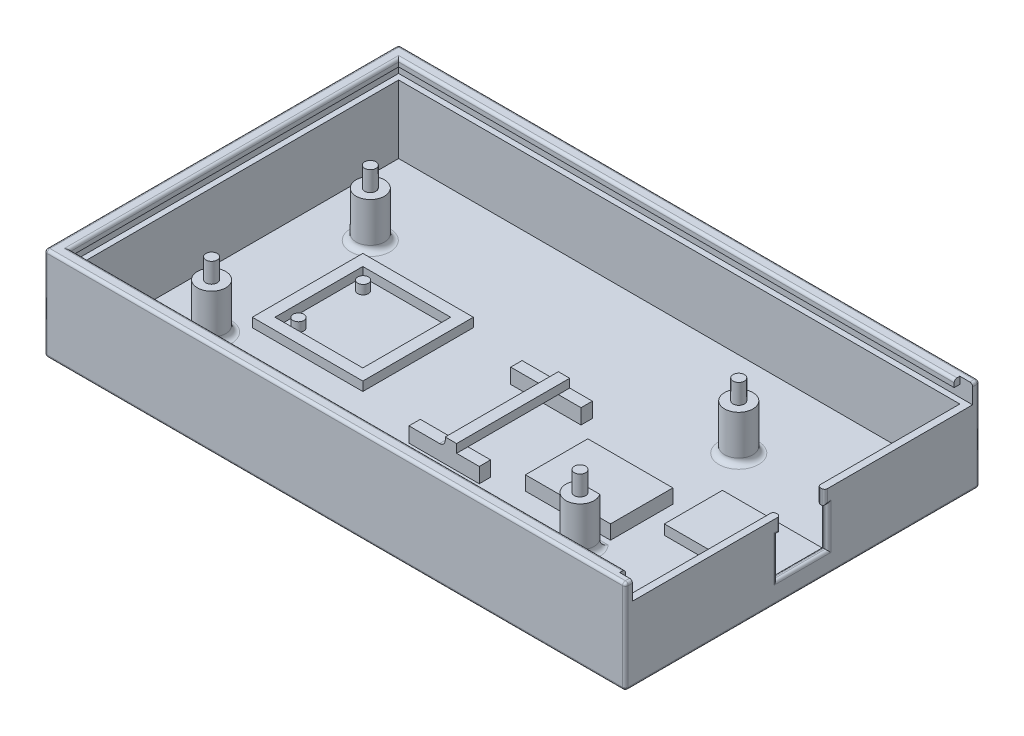
SolidWorks part; units mm, degrees
ref_plane "正面" through (0, 0, 0) normal (0, 0, 1) x (1, 0, 0)
ref_plane "平面" through (0, 0, 0) normal (0, 1, 0) x (1, 0, 0)
ref_plane "右側面" through (0, 0, 0) normal (1, 0, 0) x (0, 0, -1)
sketch "ｽｹｯﾁ1" plane through (0, 0, 0) normal (0, 1, 0) x (1, 0, 0)
  line L1 (-50, -30) -> (50, -30)
  line L2 (-50, -30) -> (-50, 30)
  line L3 (-50, 30) -> (50, 30)
  line L4 (50, -30) -> (50, 30)
  line L5 (-50, -30) -> (50, 30) construction
  line L6 (-50, 30) -> (50, -30) construction
  circle A0 centre (-32.7055, 14.1816) radius 1.25 construction
  circle A1 centre (32.2945, 14.1816) radius 1.25 construction
  circle A2 centre (32.2945, -13.8184) radius 1.25 construction
  circle A3 centre (-32.7055, -13.8184) radius 1.25 construction
  point P0 (0, 0)
  dimension "D3" = 2.5
  dimension "D4" = 28
  dimension "D1" = 60
  dimension "D2" = 100
  dimension "D5" = 65
extrude "ﾎﾞｽ - 押し出し1" add sketch "ｽｹｯﾁ1" along normal blind 1.25
sketch "ｽｹｯﾁ2" plane through (0, 1.25, 0) normal (0, 1, 0) x (1, 0, 0)
  line L0 (65.1569, 0) -> (-85.7895, 0) construction
  line L1 (-2.5, -60.5442) -> (-2.5, 68.5251) construction
  line L3 (-50, 30) -> (-50, -30) construction
  circle A0 centre (-39, 14) radius 1
  circle A1 centre (26, 14) radius 1
  circle A2 centre (26, -14) radius 1
  circle A3 centre (-39, -14) radius 1
  dimension "D1" = 2
  dimension "D4" = 11
  dimension "D5" = 28.5
  dimension "D2" = 65
  dimension "D3" = 28
extrude "ﾎﾞｽ - 押し出し2" add sketch "ｽｹｯﾁ2" along normal blind 11.5
sketch "ｽｹｯﾁ4" plane through (0, 0, 0) normal (0, -1, 0) x (1, 0, 0)
  line L0 (-50, 30) -> (50, 30) construction
  line L1 (-51.25, -31.25) -> (51.25, -31.25)
  line L2 (-51.25, -31.25) -> (-51.25, 31.25)
  line L3 (-51.25, 31.25) -> (51.25, 31.25)
  line L4 (51.25, -31.25) -> (51.25, 31.25)
  line L5 (-51.25, -31.25) -> (51.25, 31.25) construction
  line L6 (-51.25, 31.25) -> (51.25, -31.25) construction
  line L7 (-50, -30) -> (50, -30)
  line L8 (-50, -30) -> (-50, 30)
  line L9 (-50, 30) -> (50, 30)
  line L10 (50, -30) -> (50, 30)
  line L11 (-50, -30) -> (50, 30) construction
  line L12 (-50, 30) -> (50, -30) construction
  line L13 (50, 30) -> (50, -30) construction
  point P0 (0, 0)
  point P6 (0, 0)
  dimension "D1" = 1.25
  dimension "D2" = 1.25
extrude "ﾎﾞｽ - 押し出し3" add sketch "ｽｹｯﾁ4" against normal blind 16.5
sketch "ｽｹｯﾁ6" plane through (0, 1.25, 0) normal (0, 1, 0) x (1, 0, 0)
  circle A0 centre (-39, 14) radius 2.5
  circle A3 centre (26, 14) radius 2.5
  circle A4 centre (26, -14) radius 2.5
  circle A5 centre (-39, -14) radius 2.5
  dimension "D1" = 5
extrude "ﾎﾞｽ - 押し出し4" add sketch "ｽｹｯﾁ6" along normal blind 8
sketch "ｽｹｯﾁ7" plane through (0, 1.25, 0) normal (0, 1, 0) x (1, 0, 0)
  line L0 (38.8649, 0) -> (-35.9859, 0) construction
  line L1 (-11.25, 55.2292) -> (-11.25, -51.2381) construction
  line L2 (50, -30) -> (50, 30) construction
  circle A0 centre (-11.25, -14) radius 1.35
  circle A1 centre (-11.25, 14) radius 1.35
  dimension "D1" = 2.7
  dimension "D3" = 61.25
  dimension "D2" = 28
extrude "ﾎﾞｽ - 押し出し5" [suppressed] add sketch "ｽｹｯﾁ7" along normal blind 12
sketch "ｽｹｯﾁ8" [suppressed] plane through (0, 1.25, 0) normal (0, 1, 0) x (1, 0, 0)
  circle A0 centre (-11.25, 14) radius 3
  circle A1 centre (-11.25, -14) radius 3
  dimension "D1" = 6
extrude "ﾎﾞｽ - 押し出し6" [suppressed] add sketch "ｽｹｯﾁ8" along normal blind 3
fillet "ﾌｨﾚｯﾄ1" [suppressed] radius 1
sketch "ｽｹｯﾁ10" plane through (51.25, 0, 0) normal (1, 0, 0) x (0, 0, -1)
  line L0 (31.25, 16.5) -> (-31.25, 16.5) construction
  line L1 (-30, 16.5) -> (30, 16.5)
  line L2 (-30, 16.5) -> (-30, 13.25)
  line L3 (-30, 13.25) -> (30, 13.25)
  line L4 (30, 16.5) -> (30, 13.25)
  line L5 (-31.25, 16.5) -> (-31.25, 0) construction
  line L6 (31.25, 16.5) -> (31.25, 0) construction
  dimension "D1" = 3.25
  dimension "D2" = 0
  dimension "D3" = 1.25
  dimension "D4" = 1.25
extrude "ｶｯﾄ - 押し出し2" cut sketch "ｽｹｯﾁ10" against normal blind 101.25
sketch "ｽｹｯﾁ11" plane through (51.25, 0, 0) normal (1, 0, 0) x (0, 0, -1)
  line L1 (-30, 16.5) -> (-29, 16.5)
  line L2 (-30, 16.5) -> (-30, 15.25)
  line L3 (-30, 15.25) -> (-29, 15.25)
  line L4 (-29, 16.5) -> (-29, 15.25)
  line L5 (30, 16.5) -> (29, 16.5)
  line L6 (30, 16.5) -> (30, 15.25)
  line L7 (30, 15.25) -> (29, 15.25)
  line L8 (29, 16.5) -> (29, 15.25)
  line L9 (-30, 13.25) -> (-29, 13.25)
  line L10 (-30, 13.25) -> (-30, 12)
  line L11 (-30, 12) -> (-29, 12)
  line L12 (-29, 13.25) -> (-29, 12)
  line L13 (29, 13.25) -> (30, 13.25)
  line L14 (29, 13.25) -> (29, 12)
  line L15 (29, 12) -> (30, 12)
  line L16 (30, 13.25) -> (30, 12)
  line L18 (-30, 13.25) -> (-30, 1.25) construction
  line L19 (30, 13.25) -> (30, 1.25) construction
  line L21 (-30, 16.5) -> (-31.25, 16.5) construction
  dimension "D1" = 1
  dimension "D2" = 1.25
  dimension "D3" = 2
extrude "ﾎﾞｽ - 押し出し8" add sketch "ｽｹｯﾁ11" against normal blind 101.25
sketch "ｽｹｯﾁ12" plane through (51.25, 0, 0) normal (1, 0, 0) x (0, 0, -1)
  line L0 (-30, 15.25) -> (-29, 15.25) construction
  line L1 (-29, 15.25) -> (-30, 15.25)
  line L2 (-29, 15.25) -> (-29, 16.5)
  line L3 (-29, 16.5) -> (-30, 16.5)
  line L4 (-30, 15.25) -> (-30, 16.5)
  line L5 (-29, 15.25) -> (-29, 16.5) construction
  line L6 (-29, 16.5) -> (-31.25, 16.5) construction
  line L7 (31.25, 16.5) -> (29, 16.5) construction
  line L8 (29, 15.25) -> (30, 15.25)
  line L9 (29, 15.25) -> (29, 16.5)
  line L10 (29, 16.5) -> (30, 16.5)
  line L11 (30, 15.25) -> (30, 16.5)
  line L12 (30, 13.25) -> (30, 15.25) construction
  line L14 (-30, 15.25) -> (-30, 13.25) construction
extrude "ｶｯﾄ - 押し出し5" cut sketch "ｽｹｯﾁ12" against normal blind 2.25
sketch "ｽｹｯﾁ13" plane through (-50, 0, 0) normal (1, 0, 0) x (0, 0, -1)
  line L1 (-29, 16.5) -> (29, 16.5)
  line L2 (-29, 16.5) -> (-29, 15.25)
  line L3 (-29, 15.25) -> (29, 15.25)
  line L4 (29, 16.5) -> (29, 15.25)
  line L5 (29, 13.25) -> (-29, 13.25)
  line L6 (29, 13.25) -> (29, 12)
  line L7 (29, 12) -> (-29, 12)
  line L8 (-29, 13.25) -> (-29, 12)
extrude "ﾎﾞｽ - 押し出し9" add sketch "ｽｹｯﾁ13" along normal blind 1
sketch "ｽｹｯﾁ14" plane through (51.25, 0, 0) normal (1, 0, 0) x (0, 0, -1)
  line L0 (-30, 13.25) -> (30, 13.25) construction
  line L1 (-4.5, 13.25) -> (4.5, 13.25)
  line L2 (-4.5, 13.25) -> (-4.5, 3.7)
  line L3 (-4.5, 3.7) -> (4.5, 3.7)
  line L4 (4.5, 13.25) -> (4.5, 3.7)
  line L5 (-4.5, 10.7) -> (-3.9, 10.7)
  line L6 (-3.9, 10.7) -> (-3.9, 13.25)
  line L7 (3.9, 13.25) -> (3.9, 10.7)
  line L8 (0, 32.3195) -> (0, -16.8429) construction
  line L9 (3.9, 10.7) -> (4.5, 10.7)
  line L10 (-30, 1.25) -> (30, 1.25) construction
  line M3 (30, 13.25) -> (-30, 13.25)
  dimension "D1" = 9
  dimension "D2" = 2.45
  dimension "D3" = 7.8
  dimension "D4" = 7
extrude "ｶｯﾄ - 押し出し6" cut sketch "ｽｹｯﾁ14" against normal blind 1.75 contours L8 L6 L5 L2 L3 M3 | L1 L8 L3 L4 L9 L7
fillet "ﾌｨﾚｯﾄ2" radius 0.5 30 edges at (-51.25, 8.25, 31.25) (0, 16.5, 31.25) (51.25, 8.25, 31.25) (0, 0, 31.25) (0, 16.5, -29) (-49, 16.5, 0) (0, 16.5, 29) (50, 7.2, -4.5) (51.25, 7.2, -4.5) (50, 3.7, 0) (51.25, 3.7, 0) (50, 7.2, 4.5) (51.25, 7.2, 4.5) (51.25, 0, 0) (-51.25, 0, 0) (-51.25, 16.5, 0) (0, 0, -31.25) (0, 16.5, -31.25) (-51.25, 8.25, -31.25) (51.25, 8.25, -31.25) (51.25, 16.5, -30.625) (51.25, 16.5, 30.625) (50, 10.7, -4.2) (50, 10.7, 4.2) (50, 11.975, -3.9) (50, 11.975, 3.9) (51.25, 11.975, 3.9) (51.25, 11.975, -3.9) (51.25, 10.7, -4.2) (51.25, 10.7, 4.2)
sketch "ｽｹｯﾁ15" plane through (0, 1.25, 0) normal (0, 1, 0) x (1, 0, 0)
  line L0 (-75.1968, 0) -> (80.2345, 0) construction
  line L1 (-16.5685, 9.75) -> (-36.0685, 9.75)
  line L2 (-18.5685, -7.75) -> (-34.0685, -7.75)
  line L3 (-18.5685, -7.75) -> (-18.5685, 7.75)
  line L4 (-18.5685, 7.75) -> (-34.0685, 7.75)
  line L5 (-34.0685, -7.75) -> (-34.0685, 7.75)
  line L6 (-18.5685, -7.75) -> (-34.0685, 7.75) construction
  line L7 (-18.5685, 7.75) -> (-34.0685, -7.75) construction
  line L8 (-36.0685, -9.75) -> (-36.0685, 9.75)
  line L9 (-16.5685, -9.75) -> (-36.0685, -9.75)
  line L10 (-16.5685, -9.75) -> (-16.5685, 9.75)
  circle A0 centre (-31.9685, 5.7) radius 0.95
  circle A1 centre (-31.9685, -5.7) radius 0.95
  point P3 (-26.3185, 0)
  dimension "D3" = 1.9
  dimension "D1" = 15.5
  dimension "D4" = 11.4
  dimension "D5" = 2.1
  dimension "D2" = 2
extrude "ﾎﾞｽ - 押し出し11" add sketch "ｽｹｯﾁ15" along normal blind 1.6 contours A1 | L9 L10 L1 L8 L2 L5 L4 L3 | A0
sketch "ｽｹｯﾁ16" plane through (0, 1.25, 0) normal (0, 1, 0) x (1, 0, 0)
  line L0 (-15.3257, 0) -> (93.0087, 0) construction
  line L1 (50, -30) -> (50, 30) construction
  line L2 (32, -5.125) -> (50, -5.125)
  line L3 (32, -5.125) -> (32, 5.125)
  line L4 (32, 5.125) -> (50, 5.125)
  line L5 (50, -5.125) -> (50, 5.125)
  line L6 (32, -5.125) -> (50, 5.125) construction
  line L7 (32, 5.125) -> (50, -5.125) construction
  line L9 (13, -10.625) -> (28, -10.625)
  line L10 (13, -10.625) -> (13, 0.375)
  line L11 (13, 0.375) -> (28, 0.375)
  line L12 (28, -10.625) -> (28, 0.375)
  point P3 (41, 0)
  dimension "D1" = 10.25
  dimension "D2" = 18
  dimension "D3" = 11
  dimension "D4" = 15
  dimension "D5" = 4
  dimension "D6" = 5.5
extrude "ﾎﾞｽ - 押し出し12" add sketch "ｽｹｯﾁ16" along normal blind 1.75
sketch "ｽｹｯﾁ17" plane through (0, 1.25, 0) normal (0, 1, 0) x (1, 0, 0)
  line L0 (-4.6, 6.375) -> (7.8, 6.375)
  line L1 (-4.6, -13.575) -> (7.8, -13.575)
  line L2 (-4.6, -13.575) -> (-4.6, -11.575)
  line L3 (-4.6, -11.575) -> (5.8, -11.575)
  line L4 (7.8, -13.575) -> (7.8, 6.375)
  line L5 (-9.6491, 0) -> (61.2015, 0) construction
  line L6 (50, 5.125) -> (32, 5.125) construction
  line L7 (32, 5.125) -> (32, -5.125) construction
  line L8 (5.8, -11.575) -> (5.8, 4.375)
  line L9 (5.8, -11.575) -> (7.8, -11.575)
  line L10 (5.8, 4.375) -> (7.8, 4.375)
  line L11 (5.8, 4.375) -> (-4.6, 4.375)
  line L12 (-4.6, 6.375) -> (-4.6, 4.375)
  dimension "D1" = 2
  dimension "D2" = 2
  dimension "D3" = 10.4
  dimension "D4" = 15.95
  dimension "D5" = 0.75
  dimension "D6" = 26.2
extrude "ﾎﾞｽ - 押し出し13" add sketch "ｽｹｯﾁ17" along normal blind 2.65 contours L9 L3 L2 L1 L4 | L0 L12 L11 L10 L4
sketch "ｽｹｯﾁ19" plane through (0, 1.25, 0) normal (0, 1, 0) x (1, 0, 0)
  line L0 (23.9635, -12.55) -> (28.0365, -12.55)
  line L1 (19.5561, -14) -> (32.8323, -14) construction
  arc A0 (28.0365, -12.55) -> (23.9635, -12.55) centre (26, -14) ccw
  dimension "D1" = 2.5
  dimension "D2" = 1.45
extrude "ｶｯﾄ - 押し出し7" cut sketch "ｽｹｯﾁ19" along normal through all
fillet "ﾌｨﾚｯﾄ3" radius 1 5 edges at (26, 1.25, 12.55) (-39, 1.25, -16.5) (26, 1.25, -16.5) (26, 1.25, 16.5) (-39, 1.25, 11.5)
sketch "ｽｹｯﾁ20" plane through (0, 3.9, 0) normal (0, 1, 0) x (-1, 0, 0)
  line L1 (-1.8, 11.575) -> (-3.8, 11.575)
  line L2 (-1.8, 11.575) -> (-1.8, 13.575)
  line L3 (-1.8, 13.575) -> (-3.8, 13.575)
  line L4 (-3.8, 11.575) -> (-3.8, 13.575)
  line L7 (-1.8, -4.375) -> (-3.8, -4.375)
  line L8 (-1.8, -4.375) -> (-1.8, -6.375)
  line L9 (-1.8, -6.375) -> (-3.8, -6.375)
  line L10 (-3.8, -4.375) -> (-3.8, -6.375)
  line L13 (-7.8, 13.575) -> (-7.8, 11.575) construction
  line L14 (4.6, 11.575) -> (-7.8, 11.575) construction
  line L15 (4.6, 13.575) -> (-7.8, 13.575) construction
  line L16 (-7.8, -4.375) -> (4.6, -4.375) construction
  line L17 (4.6, -6.375) -> (-7.8, -6.375) construction
  line L19 (-1.8, -4.375) -> (-3.8, -4.375)
  line L20 (-1.8, -4.375) -> (-1.8, 11.575)
  line L21 (-1.8, 11.575) -> (-3.8, 11.575)
  line L22 (-3.8, -4.375) -> (-3.8, 11.575)
  line M21 (-7.8, 11.575) -> (4.6, 11.575)
  line M23 (4.6, 13.575) -> (-7.8, 13.575)
  dimension "D1" = 2
  dimension "D2" = 4
extrude "ﾎﾞｽ - 押し出し14" add sketch "ｽｹｯﾁ20" along normal blind 1.5 contours L4 L2 M21 M23 | L22 L7 L20 M21 | L7 L10 L9 L8
sketch "ｽｹｯﾁ21" plane through (0, 3, 0) normal (0, 1, 0) x (1, 0, 0)
  line L1 (13, 0.375) -> (28, 0.375)
  line L2 (13, 0.375) -> (13, -10.625)
  line L3 (13, -10.625) -> (28, -10.625)
  line L4 (28, 0.375) -> (28, -10.625)
extrude "ﾎﾞｽ - 押し出し15" add sketch "ｽｹｯﾁ21" along normal blind 0.75
sketch "ｽｹｯﾁ22" plane through (0, 1.25, 0) normal (0, 1, 0) x (1, 0, 0)
  line L0 (50, 30) -> (-50, 30) construction
  line L1 (50, -30) -> (-50, -30)
  line L2 (50, -30) -> (50, 30)
  line L3 (50, 30) -> (-50, 30)
  line L4 (-50, -30) -> (-50, 30)
  line L6 (50, -29) -> (-49, -29)
  line L7 (50, -29) -> (50, 29)
  line L8 (50, 29) -> (-49, 29)
  line L9 (-49, -29) -> (-49, 29)
  line M16 (50, 30) -> (-50, 30)
  line M17 (-50, 30) -> (-50, -30)
  line M18 (-50, -30) -> (50, -30)
  line M19 (50, -30) -> (50, -5.125)
  dimension "D1" = 1
  dimension "D2" = 1
  dimension "D3" = 1
extrude "ﾎﾞｽ - 押し出し16" add sketch "ｽｹｯﾁ22" along normal up to vertex contours L6 L9 L8 L2 M16 M17 M18 M19
fillet "ﾌｨﾚｯﾄ4" radius 1 2 edges
